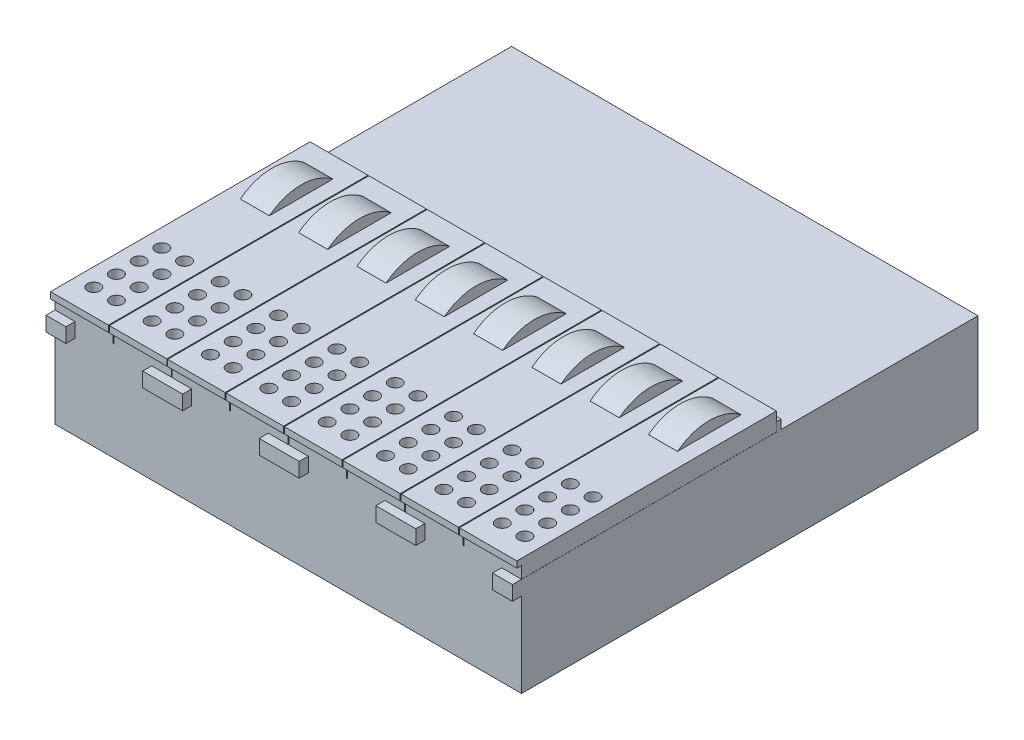
SolidWorks part; units mm, degrees
ref_plane "Front Plane" through (0, 0, 0) normal (0, 0, 1) x (1, 0, 0)
ref_plane "Top Plane" through (0, 0, 0) normal (0, 1, 0) x (1, 0, 0)
ref_plane "Right Plane" through (0, 0, 0) normal (1, 0, 0) x (0, 0, -1)
sketch "Sketch2" plane through (0, 0, 0) normal (1, 0, 0) x (0, 0, -1)
  line L0 (0, 0) -> (0, 10.9)
  line L1 (0, 10.9) -> (-21.7, 10.9)
  line L2 (-21.7, 10.9) -> (-21.7, 11.9)
  line L3 (-21.7, 11.9) -> (-22.2, 11.9)
  line L4 (-22.2, 11.9) -> (-22.2, 12.9)
  line L5 (-22.2, 12.9) -> (-50.8, 12.9)
  line L6 (-50.8, 12.9) -> (-50.8, 12.2)
  line L7 (-50.8, 12.2) -> (-50.3, 12.2)
  line L8 (-50.3, 12.2) -> (-50.3, 10.9)
  line L9 (-50.3, 10.9) -> (-51.3, 10.9)
  line L10 (-51.3, 10.9) -> (-51.3, 9.3)
  line L11 (-51.3, 9.3) -> (-50.3, 9.3)
  line L12 (-50.3, 9.3) -> (-50.3, 0)
  line L13 (-50.3, 0) -> (0, 0)
  arc A0 (-31.5, 12.9) -> (-24.5, 12.9) centre (-28, 8.3958) cw
  point P13 (-28, 14.1)
  dimension "D1" = 50.3
  dimension "D2" = 10.9
  dimension "D3" = 1
  dimension "D4" = 0.5
  dimension "D5" = 12.9
  dimension "D6" = 10.9
  dimension "D7" = 1.6
  dimension "D8" = 28.6
  dimension "D9" = 0.5
  dimension "D10" = 0.5
  dimension "D11" = 0.7
  dimension "D12" = 7
  dimension "D13" = 1.2
  dimension "D14" = 28
extrude "Boss-Extrude1" add sketch "Sketch2" along normal blind 51.4 contours A0 L5 | L12 L13 L0 L1 L2 L3 L4 L5 L6 L7 L8 L9 L10 L11
sketch "Sketch3" plane through (0, 12.9, 0) normal (0, 1, 0) x (1, 0, 0)
  line L0 (51.4, -31.5) -> (0, -31.5) construction
  line L1 (0, -24.5) -> (6.425, -24.5)
  line L2 (0, -24.5) -> (0, -31.5)
  line L3 (0, -31.5) -> (6.425, -31.5)
  line L4 (6.425, -24.5) -> (6.425, -31.5)
  line L5 (51.4, -24.5) -> (0, -24.5) construction
  line L6 (1.6125, -24.5) -> (4.8125, -24.5)
  line L7 (1.6125, -24.5) -> (1.6125, -31.5)
  line L8 (1.6125, -31.5) -> (4.8125, -31.5)
  line L9 (4.8125, -24.5) -> (4.8125, -31.5)
  point P11 (3.2125, -24.5)
  point P12 (3.2125, -24.5)
  point P13 (1.6125, -28)
  point P14 (0, -28)
  line M8 (51.4, -31.5) -> (0, -31.5)
  dimension "D1" = 6.425
  dimension "D2" = 3.2
extrude "Cut-Extrude1" cut sketch "Sketch3" along normal up to next contours L7 L1 L2 L3 | L1 L9 L4 M8
pattern_linear "LPattern1" count 8 spacing 6.425 along (1, 0, 0) of "Cut-Extrude1"
sketch "Sketch4" plane through (0, 0, 51.3) normal (0, 0, 1) x (1, 0, 0)
  line L0 (51.4, 10.9) -> (0, 10.9) construction
  line L1 (2.2, 10.9) -> (-2.2, 10.9)
  line L2 (2.2, 10.9) -> (2.2, 9.3)
  line L3 (2.2, 9.3) -> (-2.2, 9.3)
  line L4 (-2.2, 10.9) -> (-2.2, 9.3)
  line L5 (51.4, 9.3) -> (0, 9.3) construction
  line L6 (10.65, 10.9) -> (15.05, 10.9)
  line L7 (10.65, 10.9) -> (10.65, 9.3)
  line L8 (10.65, 9.3) -> (15.05, 9.3)
  line L9 (15.05, 10.9) -> (15.05, 9.3)
  line L10 (0, 10.9) -> (0, 9.3) construction
  line L11 (0, 12.2) -> (0, 10.9) construction
  line L12 (2.2, 10.9) -> (10.65, 10.9)
  line L17 (2.2, 9.3) -> (10.65, 9.3)
  point P12 (0, 10.9)
  point P20 (12.85, 10.9)
  line M10 (0, 9.3) -> (51.4, 9.3)
  line M12 (51.4, 10.9) -> (0, 10.9)
  dimension "D1" = 12.85
  dimension "D2" = 4.4
extrude "Cut-Extrude2" cut sketch "Sketch4" against normal up to surface (1 mm away) contours L7 L2 M12 M10 up to face at (25.7, 11.55, 50.3)
pattern_linear "LPattern2" count 8 spacing 12.85 along (1, 0, 0) of "Cut-Extrude2"
sketch "Sketch5" plane through (0, 12.9, 0) normal (0, 1, 0) x (1, 0, 0)
  line L0 (51.4, -22.2) -> (0, -22.2) construction
  line L1 (6.38, -22.2) -> (6.48, -22.2)
  line L2 (6.38, -22.2) -> (6.38, -50.8)
  line L3 (6.38, -50.8) -> (6.48, -50.8)
  line L4 (6.48, -22.2) -> (6.48, -50.8)
  line L5 (51.4, -50.8) -> (0, -50.8) construction
  line L6 (0, -22.2) -> (0, -50.8) construction
  line L7 (1.965, -40.5) -> (4.465, -40.5) construction
  line L8 (1.965, -40.5) -> (1.965, -43) construction
  circle A0 centre (1.965, -40.5) radius 0.7
  circle A1 centre (4.465, -40.5) radius 0.7
  circle A2 centre (4.465, -43) radius 0.7
  circle A3 centre (4.465, -45.5) radius 0.7
  circle A4 centre (4.465, -48) radius 0.7
  circle A5 centre (1.965, -43) radius 0.7
  circle A6 centre (1.965, -45.5) radius 0.7
  circle A7 centre (1.965, -48) radius 0.7
  point P8 (6.43, -50.8)
  point P11 (3.215, -40.5)
  dimension "D3" = 1.4
  dimension "D1" = 0.1
  dimension "D2" = 6.43
  dimension "D6" = 90
  dimension "D7" = 2.5
  dimension "D8" = 2.5
  dimension "D9" = 3.215
  dimension "D10" = 10.3
  dimension "D4" = 2
  dimension "D5" = 4
extrude "Cut-Extrude3" cut sketch "Sketch5" against normal blind 2
pattern_linear "LPattern3" count 8 spacing 6.43 along (1, 0, 0) of "Cut-Extrude3"
